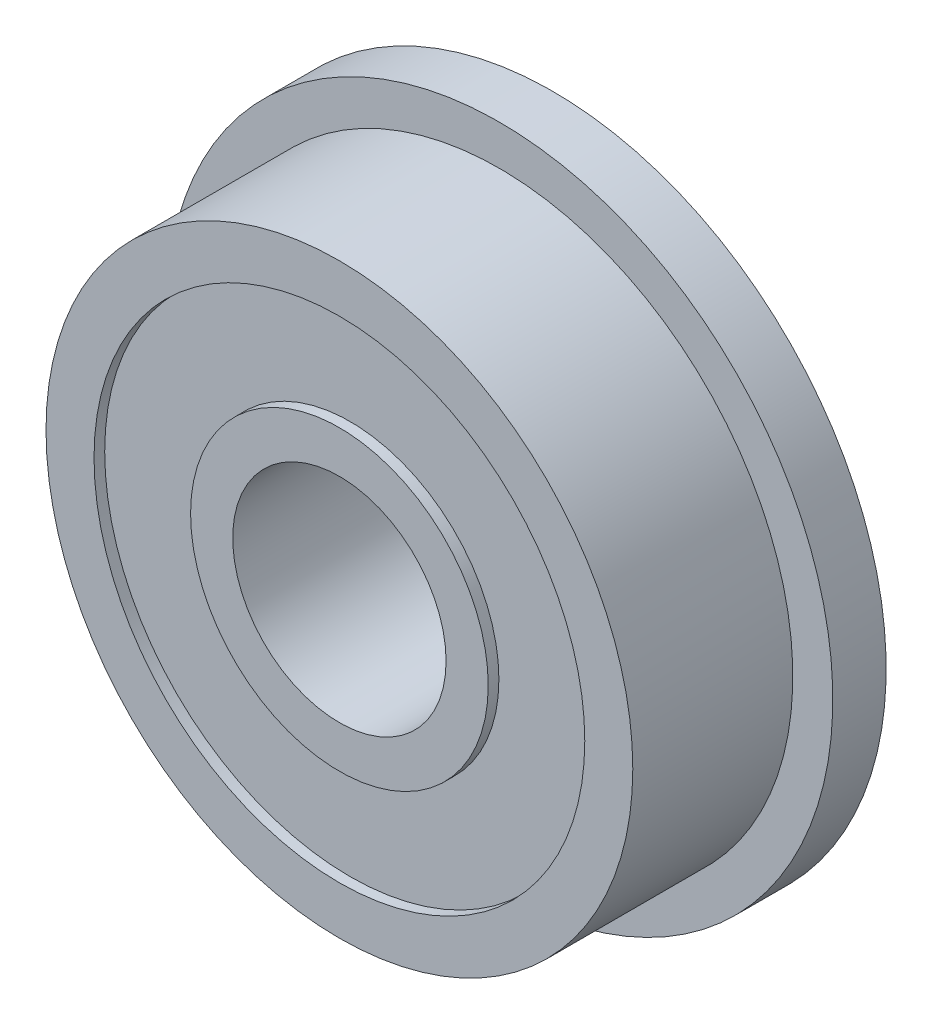
SolidWorks part; units mm, degrees
material "鉻不鏽鋼"
ref_plane "前基準面" through (0, 0, 0) normal (0, 0, 1) x (1, 0, 0)
ref_plane "上基準面" through (0, 0, 0) normal (0, 1, 0) x (1, 0, 0)
ref_plane "右基準面" through (0, 0, 0) normal (1, 0, 0) x (0, 0, -1)
sketch "草圖1" plane through (0, 0, 0) normal (0, 0, 1) x (1, 0, 0)
  circle A0 centre (0, 0) radius 5.5
  dimension "D1" = 11
extrude "填料-伸長1" add sketch "草圖1" along normal mid plane 4
sketch "草圖4" plane through (0, 0, -2) normal (0, 0, -1) x (-1, 0, 0)
  circle A0 centre (0, 0) radius 6.25
  dimension "D1" = 12.5
extrude "填料-伸長2" add sketch "草圖4" against normal blind 1
sketch "草圖2" plane through (0, 0, 2) normal (0, 0, 1) x (1, 0, 0)
  circle A0 centre (0, 0) radius 2
  dimension "D1" = 4
extrude "除料-伸長1" cut sketch "草圖2" against normal through all
sketch "草圖3" plane through (0, 0, 2) normal (0, 0, 1) x (1, 0, 0)
  circle A0 centre (0, 0) radius 2.79
  circle A1 centre (0, 0) radius 4.6
  dimension "D1" = 9.2
  dimension "D2" = 5.58
extrude "除料-伸長2" cut sketch "草圖3" against normal blind 0.2
mirror "鏡射1" about plane through (0, 0, 0) normal (0, 0, 1) of "除料-伸長2"
